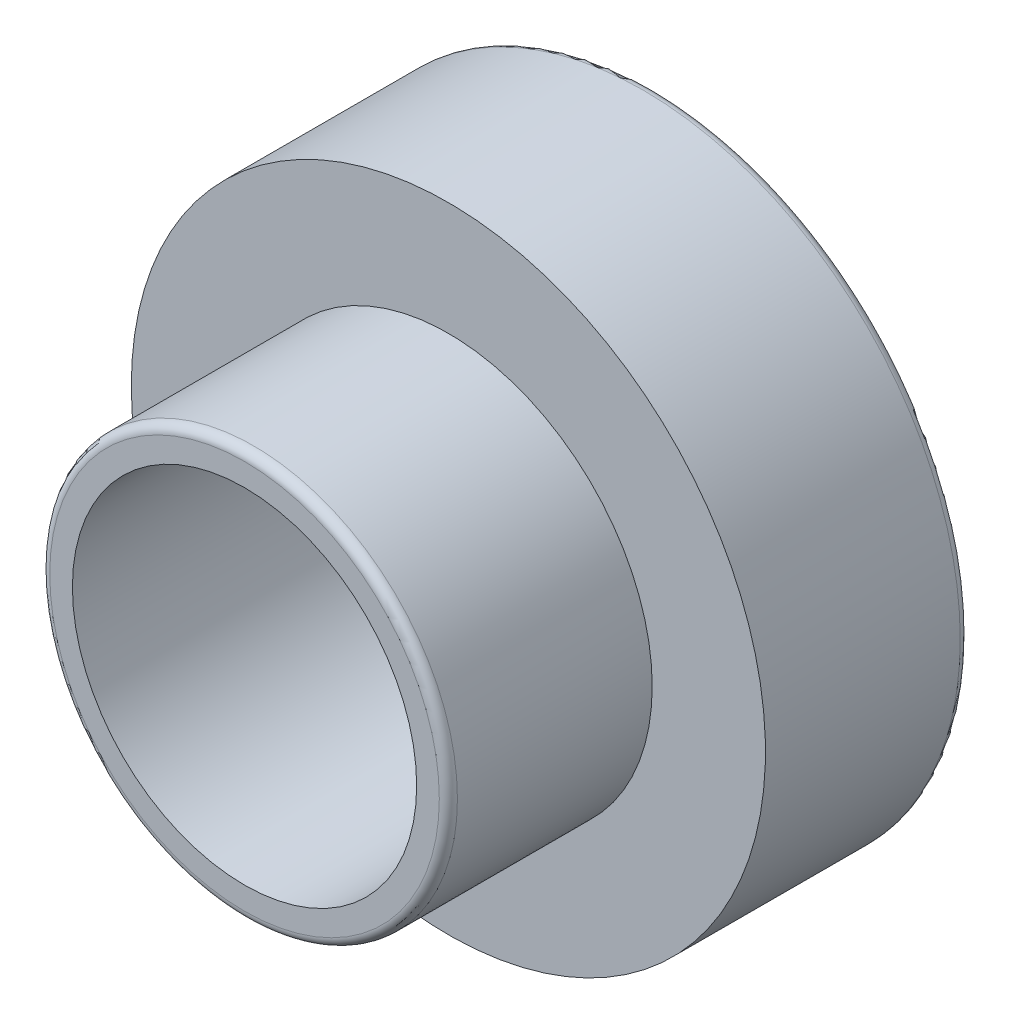
SolidWorks part; units mm, degrees
ref_plane "前视基准面" through (0, 0, 0) normal (0, 0, 1) x (1, 0, 0)
ref_plane "上视基准面" through (0, 0, 0) normal (0, 1, 0) x (1, 0, 0)
ref_plane "右视基准面" through (0, 0, 0) normal (1, 0, 0) x (0, 0, -1)
sketch "草图1" plane through (0, 0, 0) normal (0, 0, 1) x (1, 0, 0)
  circle A0 centre (0, 0) radius 70
  dimension "D1" = 140
extrude "凸台-拉伸1" add sketch "草图1" along normal blind 90
sketch "草图2" plane through (0, 0, 90) normal (0, 0, 1) x (1, 0, 0)
  circle A0 centre (0, 0) radius 38
  dimension "D1" = 76
extrude "切除-拉伸1" cut sketch "草图2" against normal through all
sketch "草图3" plane through (0, 0, 90) normal (0, 0, 1) x (1, 0, 0)
  circle A1 centre (0, 0) radius 70 construction
  circle A2 centre (0, 0) radius 45
  circle A3 centre (0, 0) radius 70
  dimension "D1" = 90
extrude "切除-拉伸2" cut sketch "草图3" against normal blind 45
fillet "圆角1" radius 2 2 edges at (70, 0, 0) (45, 0, 90)
